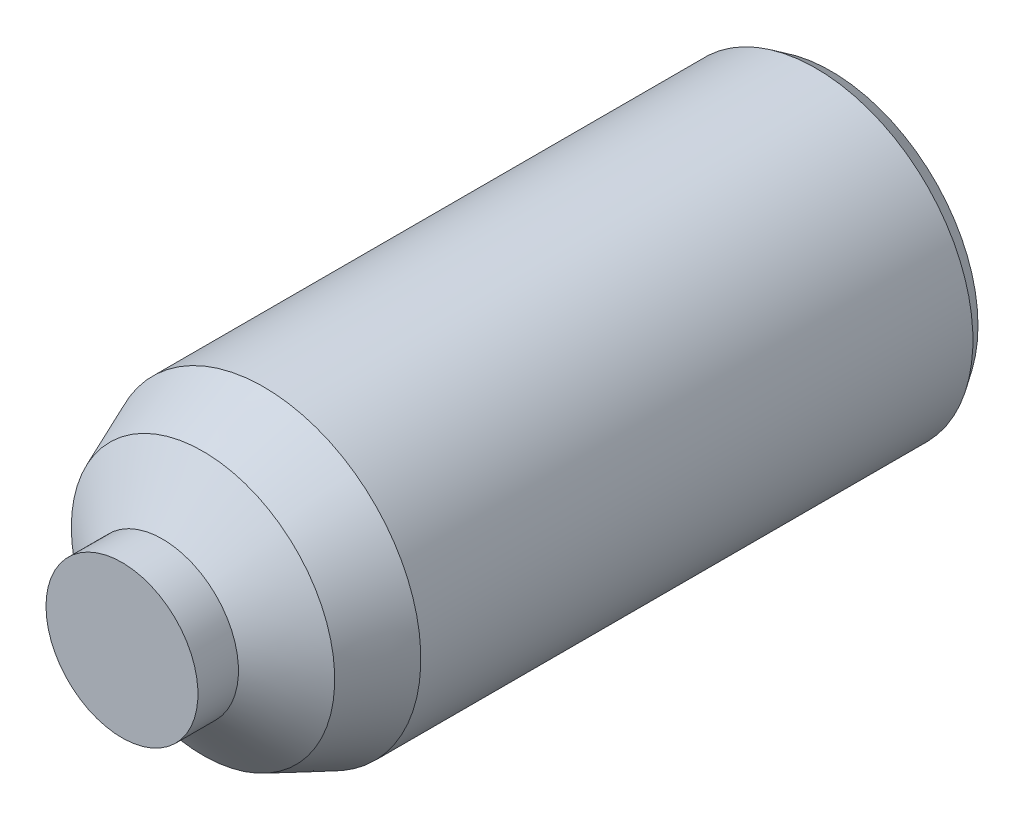
SolidWorks part; units mm, degrees
material "PE High Density"
ref_plane "Front Plane" through (0, 0, 0) normal (0, 0, 1) x (1, 0, 0)
ref_plane "Top Plane" through (0, 0, 0) normal (0, 1, 0) x (1, 0, 0)
ref_plane "Right Plane" through (0, 0, 0) normal (1, 0, 0) x (0, 0, -1)
sketch "Revolve profile 1" plane through (0, 0, 0) normal (0, 1, 0) x (1, 0, 0)
  line L0 (0, -140) -> (0, 0)
  line L1 (0, 0) -> (29, 0)
  line L2 (29, 0) -> (31, -3)
  line L3 (31, -3) -> (31, -112)
  line L4 (31, -112) -> (26, -124)
  line L5 (26, -124) -> (15, -132)
  line L6 (15, -132) -> (15, -140)
  line L7 (15, -140) -> (0, -140)
  line L8 (0, 5) -> (0, -145) construction
  dimension "D1" = 2
  dimension "D2" = 5
  dimension "D3" = 16
  dimension "D4" = 31
  dimension "D5" = 3
  dimension "D6" = 112
  dimension "D7" = 124
  dimension "D8" = 132
  dimension "D9" = 140
revolve "Revolve 1" add sketch "Revolve profile 1" angle 360 about L8
